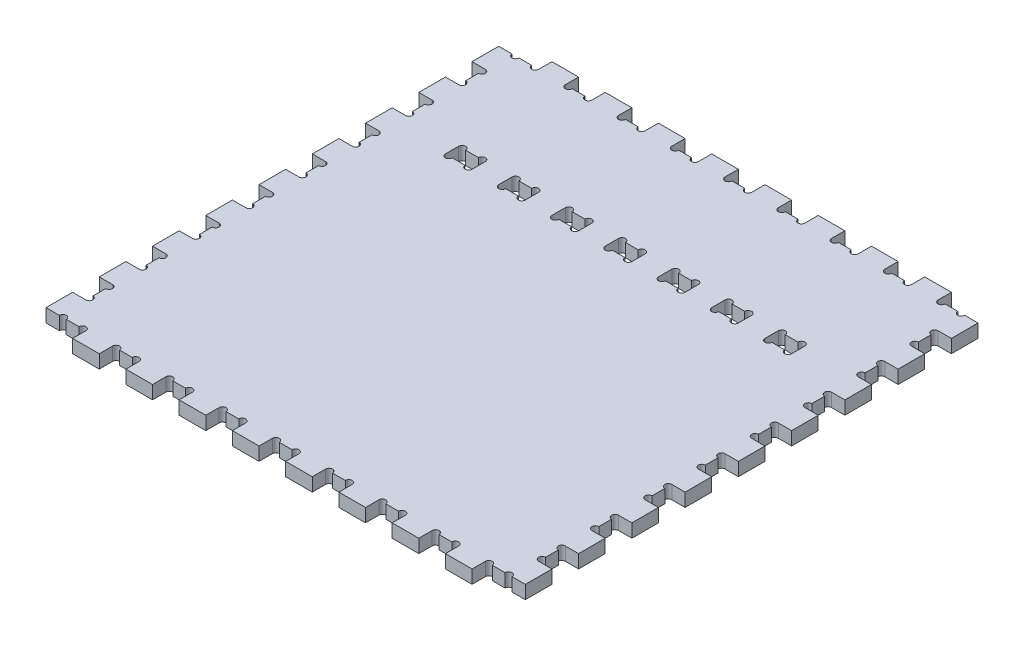
SolidWorks part; units mm, degrees
ref_plane "Front Plane" through (0, 0, 0) normal (0, 0, 1) x (1, 0, 0)
ref_plane "Top Plane" through (0, 0, 0) normal (0, 1, 0) x (1, 0, 0)
ref_plane "Right Plane" through (0, 0, 0) normal (1, 0, 0) x (0, 0, -1)
sketch "Sketch1" plane through (0, 0, 0) normal (0, 1, 0) x (1, 0, 0)
  line L1 (228.6, -228.6) -> (-228.6, -228.6)
  line L2 (228.6, -228.6) -> (228.6, 228.6)
  line L3 (228.6, 228.6) -> (-228.6, 228.6)
  line L4 (-228.6, -228.6) -> (-228.6, 228.6)
  line L5 (228.6, -228.6) -> (-228.6, 228.6) construction
  line L6 (228.6, 228.6) -> (-228.6, -228.6) construction
  point P0 (0, 0)
  dimension "D1" = 457.2
  dimension "D2" = 457.2
extrude "Boss-Extrude1" add sketch "Sketch1" along normal blind 12.7
sketch "Sketch2" plane through (0, 12.7, 0) normal (0, 1, 0) x (1, 0, 0)
  line L0 (228.6, 228.6) -> (-228.6, 228.6) construction
  line L1 (-215.9, 228.6) -> (-190.5, 228.6)
  line L2 (-215.9, 228.6) -> (-215.9, 215.9)
  line L3 (-215.9, 215.9) -> (-190.5, 215.9)
  line L4 (-190.5, 228.6) -> (-190.5, 215.9)
  line L5 (-215.9, 215.9) -> (-228.6, 215.9) construction
  line L6 (-228.6, 228.6) -> (-228.6, -228.6) construction
  circle A0 centre (-212.598, 215.9) radius 3.302
  circle A1 centre (-193.802, 215.9) radius 3.302
  line M8 (228.6, 228.6) -> (-228.6, 228.6)
  dimension "D3" = 6.604
  dimension "D4" = 6.604
  dimension "D1" = 25.4
  dimension "D2" = 12.7
  dimension "D5" = 12.7
extrude "Cut-Extrude1" cut sketch "Sketch2" against normal blind 12.7 contours A1 L4 L2 A0 L3 M8 | L3 A0 | L3 A1 | L3 A1 | L3 A0
pattern_linear "LPattern1" count 9 spacing 50.8 along (1, 0, 0) of "Cut-Extrude1"
ref_plane "Plane1" through (0, 0, 0) normal (0, 0, -1) x (-1, 0, 0)
ref_plane "Plane2" through (0, 0, 0) normal (-1, 0, 0) x (0, 0, 1)
mirror "Mirror1" about plane through (0, 0, 0) normal (0, 0, -1) of "LPattern1", "Cut-Extrude1"
sketch "Sketch3" plane through (0, 12.7, 0) normal (0, 1, 0) x (1, 0, 0)
  line L1 (-228.6, 228.6) -> (-215.9, 228.6)
  line L2 (-228.6, 228.6) -> (-228.6, 215.9)
  line L3 (-228.6, 215.9) -> (-215.9, 215.9)
  line L4 (-215.9, 228.6) -> (-215.9, 215.9)
extrude "Cut-Extrude2" cut sketch "Sketch3" against normal through all
mirror "Mirror2" about plane through (0, 0, 0) normal (-1, 0, 0) of "Cut-Extrude2"
mirror "Mirror3" about plane through (0, 0, 0) normal (0, 0, -1) of "Mirror2", "Cut-Extrude2"
sketch "Sketch4" plane through (0, 12.7, 0) normal (0, 1, 0) x (1, 0, 0)
  line L0 (-228.6, 215.9) -> (-228.6, -215.9) construction
  line L1 (-228.6, 190.5) -> (-215.9, 190.5)
  line L2 (-228.6, 190.5) -> (-228.6, 165.1)
  line L3 (-228.6, 165.1) -> (-215.9, 165.1)
  line L4 (-215.9, 190.5) -> (-215.9, 165.1)
  line L5 (-215.9, 190.5) -> (-186.3664, 190.5) construction
  line L6 (-186.3664, 190.5) -> (-186.3664, 228.6) construction
  line L7 (-165.1, 228.6) -> (-190.5, 228.6) construction
  circle A0 centre (-215.9, 187.198) radius 3.302
  circle A1 centre (-215.9, 168.402) radius 3.302
  dimension "D3" = 6.604
  dimension "D4" = 6.604
  dimension "D1" = 12.7
  dimension "D2" = 25.4
  dimension "D5" = 38.1
extrude "Cut-Extrude3" cut sketch "Sketch4" against normal through all contours A1 L4 A0 L1 L2 L3 | L4 A0 | L4 A1 | L4 A1 | L4 A0
pattern_linear "LPattern2" count 9 spacing 50.8 along (0, 0, 1) of "Cut-Extrude3"
mirror "Mirror4" about plane through (0, 0, 0) normal (-1, 0, 0) of "LPattern2", "Cut-Extrude3"
sketch "Sketch5" plane through (0, 12.7, 0) normal (0, 1, 0) x (1, 0, 0)
  line L0 (-165.1, 114.3) -> (-165.1, 215.9) construction
  line L1 (-158.496, 114.3) -> (-146.304, 114.3)
  line L2 (-165.1, 114.3) -> (-165.1, 101.6)
  line L3 (-158.496, 101.6) -> (-146.304, 101.6)
  line L4 (-139.7, 114.3) -> (-139.7, 101.6)
  arc A0 (-158.496, 114.3) -> (-165.1, 114.3) centre (-161.798, 114.3) ccw
  arc A1 (-139.7, 114.3) -> (-146.304, 114.3) centre (-143.002, 114.3) ccw
  arc A2 (-146.304, 101.6) -> (-139.7, 101.6) centre (-143.002, 101.6) ccw
  arc A3 (-165.1, 101.6) -> (-158.496, 101.6) centre (-161.798, 101.6) ccw
  dimension "D3" = 6.604
  dimension "D1" = 25.4
  dimension "D2" = 12.7
  dimension "D4" = 101.6
extrude "Cut-Extrude4" cut sketch "Sketch5" against normal through all
pattern_linear "LPattern3" count 7 spacing 50.8 along (1, 0, 0) of "Cut-Extrude4"
